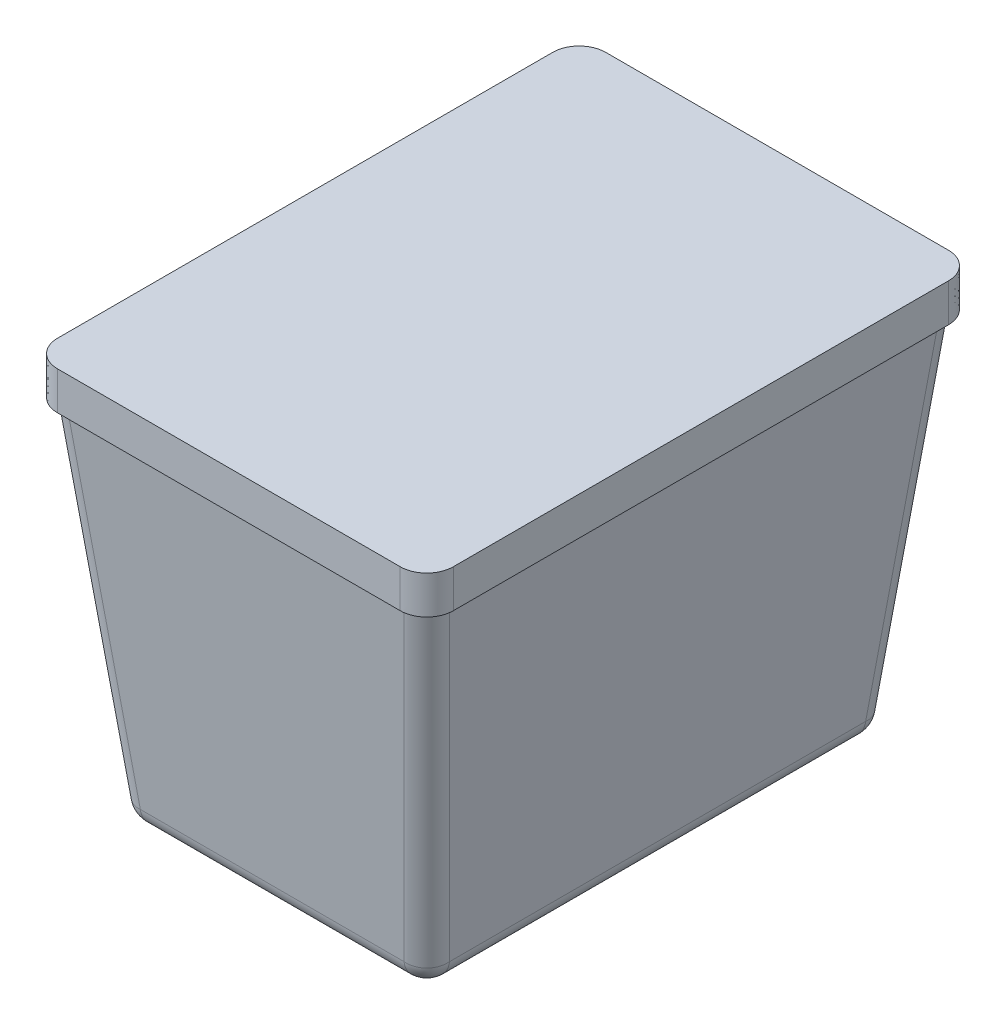
SolidWorks part; units mm, degrees
ref_plane "Alzado" through (0, 0, 0) normal (0, 0, 1) x (1, 0, 0)
ref_plane "Planta" through (0, 0, 0) normal (0, 1, 0) x (1, 0, 0)
ref_plane "Vista lateral" through (0, 0, 0) normal (1, 0, 0) x (0, 0, -1)
sketch "Croquis1" plane through (0, 0, 0) normal (0, 1, 0) x (1, 0, 0)
  line L1 (200, -300) -> (-200, -300)
  line L2 (200, -300) -> (200, 300)
  line L3 (200, 300) -> (-200, 300)
  line L4 (-200, -300) -> (-200, 300)
  line L5 (200, -300) -> (-200, 300) construction
  line L6 (200, 300) -> (-200, -300) construction
  point P0 (0, 0)
  dimension "D1" = 600
  dimension "D2" = 400
extrude "Extruir1" add sketch "Croquis1" along normal blind 520 draft 6 draft outward yes
fillet "Redondeo1" radius 30 8 edges at (0, 0, 300) (200, 0, 0) (0, 0, -300) (-200, 0, 0) (-227.3271, 260, -327.3271) (227.3271, 260, -327.3271) (227.3271, 260, 327.3271) (-227.3271, 260, 327.3271)
shell "Vaciado1" thickness 10
sketch "Croquis2" plane through (0, 520, 0) normal (0, 1, 0) x (1, 0, 0)
  line L24 (224.8185, 359.6542) -> (-224.8185, 359.6542)
  line L25 (259.6542, -324.8185) -> (259.6542, 324.8185)
  line L26 (-224.8185, -359.6542) -> (224.8185, -359.6542)
  line L27 (-259.6542, 324.8185) -> (-259.6542, -324.8185)
  line L28 (224.8185, 359.6542) -> (-224.8185, 359.6542)
  line L29 (259.6542, -324.8185) -> (259.6542, 324.8185)
  line L30 (-224.8185, -359.6542) -> (224.8185, -359.6542)
  line L31 (-259.6542, 324.8185) -> (-259.6542, -324.8185)
  spline S0 degree 3 poles (409.626, -1532.0878) (32.0766, -0.852) (-135.9095, 377.862) (-232.7137, 358.7732) (-233.8149, 358.5002) (-235.4515, 358.0079) (-235.9946, 357.83) (-237.0755, 357.446) (-237.6138, 357.2397) (-240.2615, 356.1489) (-242.2653, 355.0812) (-245.1032, 353.1931) (-246.0209, 352.5157) (-247.3539, 351.425) (-247.7906, 351.0493) (-248.6395, 350.2812) (-249.053, 349.888) (-251.067, 347.8765) (-252.5079, 346.1233) (-254.4118, 343.2761) (-255.0058, 342.2851) (-256.0832, 340.2672) (-256.5688, 339.238) (-257.8704, 336.0912) (-258.5327, 333.9145) (-284.6397, 202.615) (424.9986, 1.0365) (1649.82, -251.3643) knots -5.25859 -5.25859 -5.25859 -5.25859 0.125 0.125 0.1875 0.1875 0.21875 0.21875 0.25 0.25 0.375 0.375 0.4375 0.4375 0.46875 0.46875 0.5 0.5 0.625 0.625 0.6875 0.6875 0.75 0.75 0.875 0.875 8.020589 8.020589 8.020589 8.020589 only from (-224.8185, 359.6542) to (-259.6542, 324.8185)
  spline S1 degree 3 poles (-1632.0878, -309.626) (-100.852, 67.9234) (277.862, 235.9095) (258.7732, 332.7137) (258.5002, 333.8149) (258.0079, 335.4515) (257.83, 335.9946) (257.446, 337.0755) (257.2397, 337.6138) (256.1489, 340.2615) (255.0812, 342.2653) (253.1931, 345.1032) (252.5157, 346.0209) (251.425, 347.3539) (251.0493, 347.7906) (250.2812, 348.6395) (249.888, 349.053) (247.8765, 351.067) (246.1233, 352.5079) (243.2761, 354.4118) (242.2851, 355.0058) (240.2672, 356.0832) (239.238, 356.5688) (236.0912, 357.8704) (233.9145, 358.5327) (102.615, 384.6397) (-98.9635, -324.9986) (-351.3643, -1549.82) knots -5.25859 -5.25859 -5.25859 -5.25859 0.125 0.125 0.1875 0.1875 0.21875 0.21875 0.25 0.25 0.375 0.375 0.4375 0.4375 0.46875 0.46875 0.5 0.5 0.625 0.625 0.6875 0.6875 0.75 0.75 0.875 0.875 8.020589 8.020589 8.020589 8.020589 only from (259.6542, 324.8185) to (224.8185, 359.6542)
  spline S2 degree 3 poles (-409.626, 1532.0878) (-32.0766, 0.852) (135.9095, -377.862) (232.7137, -358.7732) (233.8149, -358.5002) (235.4515, -358.0079) (235.9946, -357.83) (237.0755, -357.446) (237.6138, -357.2397) (240.2615, -356.1489) (242.2653, -355.0812) (245.1032, -353.1931) (246.0209, -352.5157) (247.3539, -351.425) (247.7906, -351.0493) (248.6395, -350.2812) (249.053, -349.888) (251.067, -347.8765) (252.5079, -346.1233) (254.4118, -343.2761) (255.0058, -342.2851) (256.0832, -340.2672) (256.5688, -339.238) (257.8704, -336.0912) (258.5327, -333.9145) (284.6397, -202.615) (-424.9986, -1.0365) (-1649.82, 251.3643) knots -5.25859 -5.25859 -5.25859 -5.25859 0.125 0.125 0.1875 0.1875 0.21875 0.21875 0.25 0.25 0.375 0.375 0.4375 0.4375 0.46875 0.46875 0.5 0.5 0.625 0.625 0.6875 0.6875 0.75 0.75 0.875 0.875 8.020589 8.020589 8.020589 8.020589 only from (224.8185, -359.6542) to (259.6542, -324.8185)
  spline S3 degree 3 poles (1632.0878, 309.626) (100.852, -67.9234) (-277.862, -235.9095) (-258.7732, -332.7137) (-258.5002, -333.8149) (-258.0079, -335.4515) (-257.83, -335.9946) (-257.446, -337.0755) (-257.2397, -337.6138) (-256.1489, -340.2615) (-255.0812, -342.2653) (-253.1931, -345.1032) (-252.5157, -346.0209) (-251.425, -347.3539) (-251.0493, -347.7906) (-250.2812, -348.6395) (-249.888, -349.053) (-247.8765, -351.067) (-246.1233, -352.5079) (-243.2761, -354.4118) (-242.2851, -355.0058) (-240.2672, -356.0832) (-239.238, -356.5688) (-236.0912, -357.8704) (-233.9145, -358.5327) (-102.615, -384.6397) (98.9635, 324.9986) (351.3643, 1549.82) knots -5.25859 -5.25859 -5.25859 -5.25859 0.125 0.125 0.1875 0.1875 0.21875 0.21875 0.25 0.25 0.375 0.375 0.4375 0.4375 0.46875 0.46875 0.5 0.5 0.625 0.625 0.6875 0.6875 0.75 0.75 0.875 0.875 8.020589 8.020589 8.020589 8.020589 only from (-259.6542, -324.8185) to (-224.8185, -359.6542)
  spline S4 degree 3 poles (-224.8185, 359.6542) (-227.1201, 359.6542) (-229.3809, 359.4304) (-232.7137, 358.7732) (-233.8149, 358.5002) (-235.4515, 358.0079) (-235.9946, 357.83) (-237.0755, 357.446) (-237.6138, 357.2397) (-240.2615, 356.1489) (-242.2653, 355.0812) (-245.1032, 353.1931) (-246.0209, 352.5157) (-247.3539, 351.425) (-247.7906, 351.0493) (-248.6395, 350.2812) (-249.053, 349.888) (-251.067, 347.8765) (-252.5079, 346.1233) (-254.4118, 343.2761) (-255.0058, 342.2851) (-256.0832, 340.2672) (-256.5688, 339.238) (-257.8704, 336.0912) (-258.5327, 333.9145) (-259.4304, 329.3998) (-259.6542, 327.1202) (-259.6542, 324.8185) knots 0 0 0 0 0.125 0.125 0.1875 0.1875 0.21875 0.21875 0.25 0.25 0.375 0.375 0.4375 0.4375 0.46875 0.46875 0.5 0.5 0.625 0.625 0.6875 0.6875 0.75 0.75 0.875 0.875 1 1 1 1
  spline S5 degree 3 poles (259.6542, 324.8185) (259.6542, 327.1201) (259.4304, 329.3809) (258.7732, 332.7137) (258.5002, 333.8149) (258.0079, 335.4515) (257.83, 335.9946) (257.446, 337.0755) (257.2397, 337.6138) (256.1489, 340.2615) (255.0812, 342.2653) (253.1931, 345.1032) (252.5157, 346.0209) (251.425, 347.3539) (251.0493, 347.7906) (250.2812, 348.6395) (249.888, 349.053) (247.8765, 351.067) (246.1233, 352.5079) (243.2761, 354.4118) (242.2851, 355.0058) (240.2672, 356.0832) (239.238, 356.5688) (236.0912, 357.8704) (233.9145, 358.5327) (229.3998, 359.4304) (227.1202, 359.6542) (224.8185, 359.6542) knots 0 0 0 0 0.125 0.125 0.1875 0.1875 0.21875 0.21875 0.25 0.25 0.375 0.375 0.4375 0.4375 0.46875 0.46875 0.5 0.5 0.625 0.625 0.6875 0.6875 0.75 0.75 0.875 0.875 1 1 1 1
  spline S6 degree 3 poles (224.8185, -359.6542) (227.1201, -359.6542) (229.3809, -359.4304) (232.7137, -358.7732) (233.8149, -358.5002) (235.4515, -358.0079) (235.9946, -357.83) (237.0755, -357.446) (237.6138, -357.2397) (240.2615, -356.1489) (242.2653, -355.0812) (245.1032, -353.1931) (246.0209, -352.5157) (247.3539, -351.425) (247.7906, -351.0493) (248.6395, -350.2812) (249.053, -349.888) (251.067, -347.8765) (252.5079, -346.1233) (254.4118, -343.2761) (255.0058, -342.2851) (256.0832, -340.2672) (256.5688, -339.238) (257.8704, -336.0912) (258.5327, -333.9145) (259.4304, -329.3998) (259.6542, -327.1202) (259.6542, -324.8185) knots 0 0 0 0 0.125 0.125 0.1875 0.1875 0.21875 0.21875 0.25 0.25 0.375 0.375 0.4375 0.4375 0.46875 0.46875 0.5 0.5 0.625 0.625 0.6875 0.6875 0.75 0.75 0.875 0.875 1 1 1 1
  spline S7 degree 3 poles (-259.6542, -324.8185) (-259.6542, -327.1201) (-259.4304, -329.3809) (-258.7732, -332.7137) (-258.5002, -333.8149) (-258.0079, -335.4515) (-257.83, -335.9946) (-257.446, -337.0755) (-257.2397, -337.6138) (-256.1489, -340.2615) (-255.0812, -342.2653) (-253.1931, -345.1032) (-252.5157, -346.0209) (-251.425, -347.3539) (-251.0493, -347.7906) (-250.2812, -348.6395) (-249.888, -349.053) (-247.8765, -351.067) (-246.1233, -352.5079) (-243.2761, -354.4118) (-242.2851, -355.0058) (-240.2672, -356.0832) (-239.238, -356.5688) (-236.0912, -357.8704) (-233.9145, -358.5327) (-229.3998, -359.4304) (-227.1202, -359.6542) (-224.8185, -359.6542) knots 0 0 0 0 0.125 0.125 0.1875 0.1875 0.21875 0.21875 0.25 0.25 0.375 0.375 0.4375 0.4375 0.46875 0.46875 0.5 0.5 0.625 0.625 0.6875 0.6875 0.75 0.75 0.875 0.875 1 1 1 1
  dimension "D1" = 5
extrude "Extruir2" add sketch "Croquis2" against normal blind 40 separate body
sketch "Croquis3" plane through (0, 520, 0) normal (0, 1, 0) x (1, 0, 0)
  line L4 (-259.6542, 324.8185) -> (-259.6542, -324.8185)
  line L5 (-224.8185, -359.6542) -> (224.8185, -359.6542)
  line L6 (259.6542, -324.8185) -> (259.6542, 324.8185)
  line L7 (224.8185, 359.6542) -> (-224.8185, 359.6542)
  line L8 (-259.6542, 324.8185) -> (-259.6542, -324.8185)
  line L9 (-224.8185, -359.6542) -> (224.8185, -359.6542)
  line L10 (259.6542, -324.8185) -> (259.6542, 324.8185)
  line L11 (224.8185, 359.6542) -> (-224.8185, 359.6542)
  spline S4 degree 3 poles (409.626, -1532.0878) (32.0766, -0.852) (-135.9095, 377.862) (-232.7137, 358.7732) (-233.8149, 358.5002) (-235.4515, 358.0079) (-235.9946, 357.83) (-237.0755, 357.446) (-237.6138, 357.2397) (-240.2615, 356.1489) (-242.2653, 355.0812) (-245.1032, 353.1931) (-246.0209, 352.5157) (-247.3539, 351.425) (-247.7906, 351.0493) (-248.6395, 350.2812) (-249.053, 349.888) (-251.067, 347.8765) (-252.5079, 346.1233) (-254.4118, 343.2761) (-255.0058, 342.2851) (-256.0832, 340.2672) (-256.5688, 339.238) (-257.8704, 336.0912) (-258.5327, 333.9145) (-284.6397, 202.615) (424.9986, 1.0365) (1649.82, -251.3643) knots -5.25859 -5.25859 -5.25859 -5.25859 0.125 0.125 0.1875 0.1875 0.21875 0.21875 0.25 0.25 0.375 0.375 0.4375 0.4375 0.46875 0.46875 0.5 0.5 0.625 0.625 0.6875 0.6875 0.75 0.75 0.875 0.875 8.020589 8.020589 8.020589 8.020589 only from (-224.8185, 359.6542) to (-259.6542, 324.8185)
  spline S5 degree 3 poles (1632.0878, 309.626) (100.852, -67.9234) (-277.862, -235.9095) (-258.7732, -332.7137) (-258.5002, -333.8149) (-258.0079, -335.4515) (-257.83, -335.9946) (-257.446, -337.0755) (-257.2397, -337.6138) (-256.1489, -340.2615) (-255.0812, -342.2653) (-253.1931, -345.1032) (-252.5157, -346.0209) (-251.425, -347.3539) (-251.0493, -347.7906) (-250.2812, -348.6395) (-249.888, -349.053) (-247.8765, -351.067) (-246.1233, -352.5079) (-243.2761, -354.4118) (-242.2851, -355.0058) (-240.2672, -356.0832) (-239.238, -356.5688) (-236.0912, -357.8704) (-233.9145, -358.5327) (-102.615, -384.6397) (98.9635, 324.9986) (351.3643, 1549.82) knots -5.25859 -5.25859 -5.25859 -5.25859 0.125 0.125 0.1875 0.1875 0.21875 0.21875 0.25 0.25 0.375 0.375 0.4375 0.4375 0.46875 0.46875 0.5 0.5 0.625 0.625 0.6875 0.6875 0.75 0.75 0.875 0.875 8.020589 8.020589 8.020589 8.020589 only from (-259.6542, -324.8185) to (-224.8185, -359.6542)
  spline S6 degree 3 poles (-409.626, 1532.0878) (-32.0766, 0.852) (135.9095, -377.862) (232.7137, -358.7732) (233.8149, -358.5002) (235.4515, -358.0079) (235.9946, -357.83) (237.0755, -357.446) (237.6138, -357.2397) (240.2615, -356.1489) (242.2653, -355.0812) (245.1032, -353.1931) (246.0209, -352.5157) (247.3539, -351.425) (247.7906, -351.0493) (248.6395, -350.2812) (249.053, -349.888) (251.067, -347.8765) (252.5079, -346.1233) (254.4118, -343.2761) (255.0058, -342.2851) (256.0832, -340.2672) (256.5688, -339.238) (257.8704, -336.0912) (258.5327, -333.9145) (284.6397, -202.615) (-424.9986, -1.0365) (-1649.82, 251.3643) knots -5.25859 -5.25859 -5.25859 -5.25859 0.125 0.125 0.1875 0.1875 0.21875 0.21875 0.25 0.25 0.375 0.375 0.4375 0.4375 0.46875 0.46875 0.5 0.5 0.625 0.625 0.6875 0.6875 0.75 0.75 0.875 0.875 8.020589 8.020589 8.020589 8.020589 only from (224.8185, -359.6542) to (259.6542, -324.8185)
  spline S7 degree 3 poles (-1632.0878, -309.626) (-100.852, 67.9234) (277.862, 235.9095) (258.7732, 332.7137) (258.5002, 333.8149) (258.0079, 335.4515) (257.83, 335.9946) (257.446, 337.0755) (257.2397, 337.6138) (256.1489, 340.2615) (255.0812, 342.2653) (253.1931, 345.1032) (252.5157, 346.0209) (251.425, 347.3539) (251.0493, 347.7906) (250.2812, 348.6395) (249.888, 349.053) (247.8765, 351.067) (246.1233, 352.5079) (243.2761, 354.4118) (242.2851, 355.0058) (240.2672, 356.0832) (239.238, 356.5688) (236.0912, 357.8704) (233.9145, 358.5327) (102.615, 384.6397) (-98.9635, -324.9986) (-351.3643, -1549.82) knots -5.25859 -5.25859 -5.25859 -5.25859 0.125 0.125 0.1875 0.1875 0.21875 0.21875 0.25 0.25 0.375 0.375 0.4375 0.4375 0.46875 0.46875 0.5 0.5 0.625 0.625 0.6875 0.6875 0.75 0.75 0.875 0.875 8.020589 8.020589 8.020589 8.020589 only from (259.6542, 324.8185) to (224.8185, 359.6542)
  spline S8 degree 3 poles (-224.8185, 359.6542) (-227.1201, 359.6542) (-229.3809, 359.4304) (-232.7137, 358.7732) (-233.8149, 358.5002) (-235.4515, 358.0079) (-235.9946, 357.83) (-237.0755, 357.446) (-237.6138, 357.2397) (-240.2615, 356.1489) (-242.2653, 355.0812) (-245.1032, 353.1931) (-246.0209, 352.5157) (-247.3539, 351.425) (-247.7906, 351.0493) (-248.6395, 350.2812) (-249.053, 349.888) (-251.067, 347.8765) (-252.5079, 346.1233) (-254.4118, 343.2761) (-255.0058, 342.2851) (-256.0832, 340.2672) (-256.5688, 339.238) (-257.8704, 336.0912) (-258.5327, 333.9145) (-259.4304, 329.3998) (-259.6542, 327.1202) (-259.6542, 324.8185) knots 0 0 0 0 0.125 0.125 0.1875 0.1875 0.21875 0.21875 0.25 0.25 0.375 0.375 0.4375 0.4375 0.46875 0.46875 0.5 0.5 0.625 0.625 0.6875 0.6875 0.75 0.75 0.875 0.875 1 1 1 1
  spline S9 degree 3 poles (-259.6542, -324.8185) (-259.6542, -327.1201) (-259.4304, -329.3809) (-258.7732, -332.7137) (-258.5002, -333.8149) (-258.0079, -335.4515) (-257.83, -335.9946) (-257.446, -337.0755) (-257.2397, -337.6138) (-256.1489, -340.2615) (-255.0812, -342.2653) (-253.1931, -345.1032) (-252.5157, -346.0209) (-251.425, -347.3539) (-251.0493, -347.7906) (-250.2812, -348.6395) (-249.888, -349.053) (-247.8765, -351.067) (-246.1233, -352.5079) (-243.2761, -354.4118) (-242.2851, -355.0058) (-240.2672, -356.0832) (-239.238, -356.5688) (-236.0912, -357.8704) (-233.9145, -358.5327) (-229.3998, -359.4304) (-227.1202, -359.6542) (-224.8185, -359.6542) knots 0 0 0 0 0.125 0.125 0.1875 0.1875 0.21875 0.21875 0.25 0.25 0.375 0.375 0.4375 0.4375 0.46875 0.46875 0.5 0.5 0.625 0.625 0.6875 0.6875 0.75 0.75 0.875 0.875 1 1 1 1
  spline S10 degree 3 poles (224.8185, -359.6542) (227.1201, -359.6542) (229.3809, -359.4304) (232.7137, -358.7732) (233.8149, -358.5002) (235.4515, -358.0079) (235.9946, -357.83) (237.0755, -357.446) (237.6138, -357.2397) (240.2615, -356.1489) (242.2653, -355.0812) (245.1032, -353.1931) (246.0209, -352.5157) (247.3539, -351.425) (247.7906, -351.0493) (248.6395, -350.2812) (249.053, -349.888) (251.067, -347.8765) (252.5079, -346.1233) (254.4118, -343.2761) (255.0058, -342.2851) (256.0832, -340.2672) (256.5688, -339.238) (257.8704, -336.0912) (258.5327, -333.9145) (259.4304, -329.3998) (259.6542, -327.1202) (259.6542, -324.8185) knots 0 0 0 0 0.125 0.125 0.1875 0.1875 0.21875 0.21875 0.25 0.25 0.375 0.375 0.4375 0.4375 0.46875 0.46875 0.5 0.5 0.625 0.625 0.6875 0.6875 0.75 0.75 0.875 0.875 1 1 1 1
  spline S11 degree 3 poles (259.6542, 324.8185) (259.6542, 327.1201) (259.4304, 329.3809) (258.7732, 332.7137) (258.5002, 333.8149) (258.0079, 335.4515) (257.83, 335.9946) (257.446, 337.0755) (257.2397, 337.6138) (256.1489, 340.2615) (255.0812, 342.2653) (253.1931, 345.1032) (252.5157, 346.0209) (251.425, 347.3539) (251.0493, 347.7906) (250.2812, 348.6395) (249.888, 349.053) (247.8765, 351.067) (246.1233, 352.5079) (243.2761, 354.4118) (242.2851, 355.0058) (240.2672, 356.0832) (239.238, 356.5688) (236.0912, 357.8704) (233.9145, 358.5327) (229.3998, 359.4304) (227.1202, 359.6542) (224.8185, 359.6542) knots 0 0 0 0 0.125 0.125 0.1875 0.1875 0.21875 0.21875 0.25 0.25 0.375 0.375 0.4375 0.4375 0.46875 0.46875 0.5 0.5 0.625 0.625 0.6875 0.6875 0.75 0.75 0.875 0.875 1 1 1 1
  dimension "D1" = 0
extrude "Extruir3" add sketch "Croquis3" along normal blind 10
